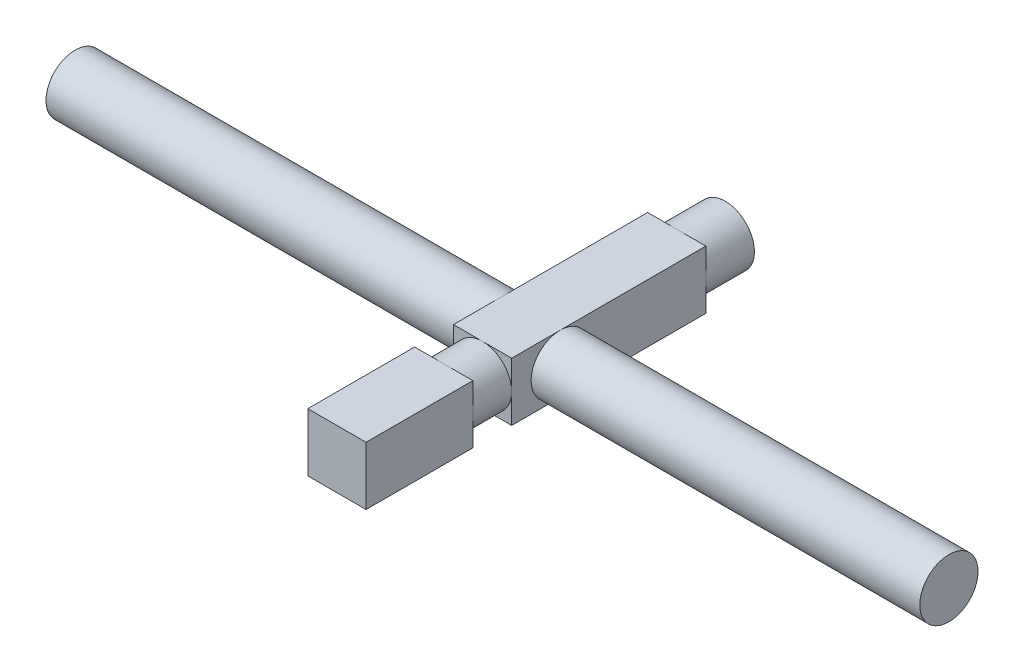
SolidWorks part; units mm, degrees
ref_plane "前视" through (0, 0, 0) normal (0, 0, 1) x (1, 0, 0)
ref_plane "上视" through (0, 0, 0) normal (0, 1, 0) x (1, 0, 0)
ref_plane "右视" through (0, 0, 0) normal (1, 0, 0) x (0, 0, -1)
sketch "草图1" plane through (0, 0, 0) normal (0, 0, 1) x (1, 0, 0)
  line L0 (-46.966, 0) -> (43.034, 0)
  line L1 (43.034, 0) -> (43.034, 3)
  line L2 (43.034, 3) -> (-46.966, 3)
  line L3 (-46.966, 3) -> (-46.966, 0)
  dimension "D1" = 90
  dimension "D2" = 3
revolve "旋转1" add sketch "草图1" angle 360 about L0
sketch "草图2" plane through (0, 0, 0) normal (1, 0, 0) x (0, 0, -1)
  line L0 (-20, 0) -> (20, 0) construction
  line L1 (20, -3) -> (20, 3)
  line L2 (20, 3) -> (-20, 3)
  line L3 (-20, 3) -> (-20, -3)
  line L4 (20, -3) -> (-20, -3)
  dimension "D1" = 3
  dimension "D2" = 20
  dimension "D3" = 20
extrude "凸台-拉伸1" add sketch "草图2" along normal blind 3 and the other way blind 3
sketch "草图3" plane through (0, 0, -20) normal (0, 0, -1) x (-1, 0, 0)
  line L1 (3, -3) -> (-3, -3)
  line L2 (3, -3) -> (3, 3)
  line L3 (3, 3) -> (-3, 3)
  line L4 (-3, -3) -> (-3, 3)
  line L5 (3, -3) -> (-3, 3) construction
  line L6 (3, 3) -> (-3, -3) construction
  circle A0 centre (0, 0) radius 3
  line M1 (3, 3) -> (-3, 3)
  line M2 (-3, 3) -> (-3, -3)
  line M3 (-3, -3) -> (3, -3)
  line M4 (3, -3) -> (3, 3)
extrude "切除-拉伸1" cut sketch "草图3" against normal blind 5 contours A0 L3 M2 | A0 L2 M1 | A0 L4 M3 | A0 L1 M4
ref_plane "基准面1" through (0, 0, 8) normal (0, 0, 1) x (1, 0, 0)
sketch "草图4" plane through (0, 0, 8) normal (0, 0, 1) x (1, 0, 0)
  line L0 (0, 3) -> (0, -3) construction
  line L1 (0, 3) -> (3, 3)
  line L2 (-3, 0) -> (-3, 3)
  line L3 (-3, 3) -> (0, 3)
  line L4 (3, 0) -> (3, 3)
  line L5 (-3, -3) -> (3, 3) construction
  line L6 (-3, 3) -> (3, -3) construction
  line L7 (-3, 0) -> (3, 0) construction
  line L8 (3, 0) -> (3, -3)
  line L9 (3, -3) -> (0, -3)
  line L10 (0, -3) -> (-3, -3)
  line L11 (-3, -3) -> (-3, 0)
  circle A0 centre (0, 0) radius 3
extrude "切除-拉伸5" cut sketch "草图4" against normal blind 3 and the other way blind 1 flip side to cut contours A0
